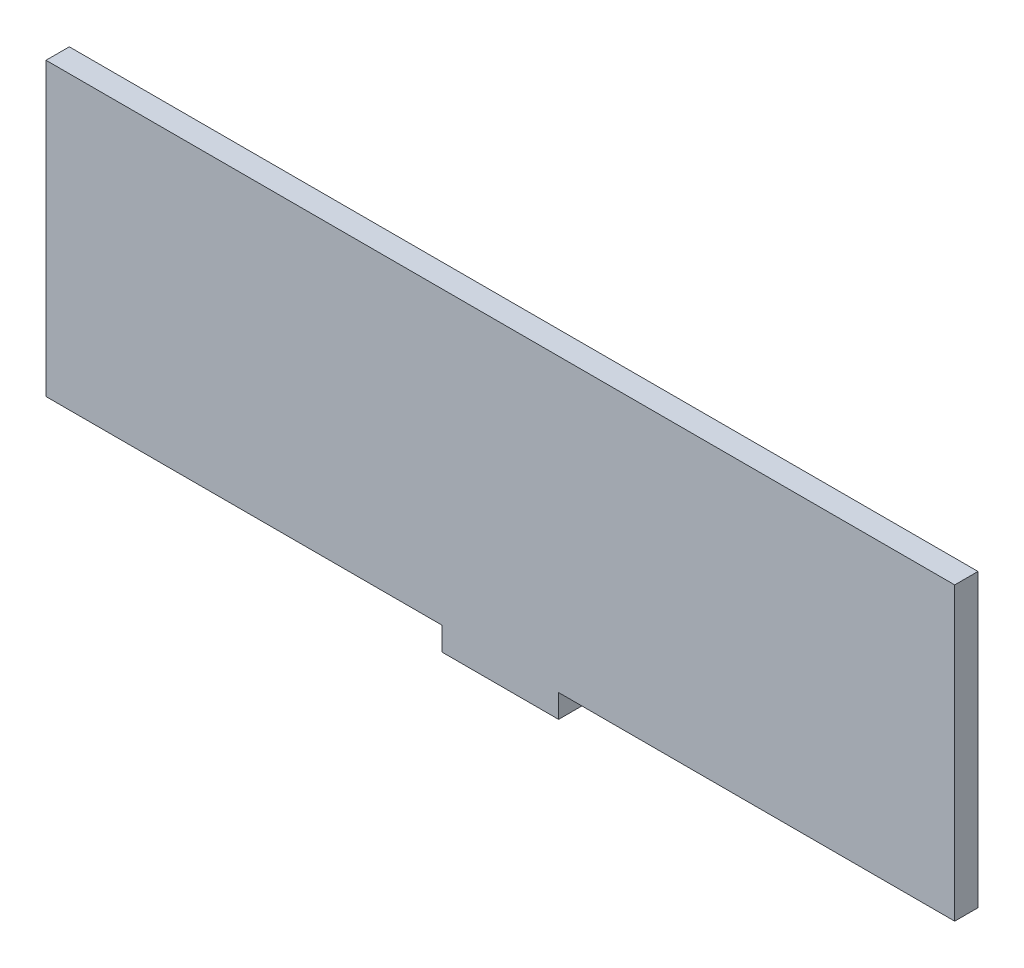
SolidWorks part; units mm, degrees
ref_plane "前视基准面" through (0, 0, 0) normal (0, 0, 1) x (1, 0, 0)
ref_plane "上视基准面" through (0, 0, 0) normal (0, 1, 0) x (1, 0, 0)
ref_plane "右视基准面" through (0, 0, 0) normal (1, 0, 0) x (0, 0, -1)
other "Configuration Table"
sketch "草图1" plane through (0, 0, 0) normal (0, 0, 1) x (1, 0, 0)
  line L0 (-39, 0) -> (39, 0) construction
  line L1 (-39, -12.5) -> (-5, -12.5)
  line L2 (-39, -12.5) -> (-39, 12.5)
  line L3 (-39, 12.5) -> (-5, 12.5)
  line L4 (39, -12.5) -> (39, 12.5)
  line L5 (-39, -12.5) -> (39, 12.5) construction
  line L6 (-39, 12.5) -> (39, -12.5) construction
  line L11 (0, 10.5) -> (5, 12.5) construction
  line L12 (-5, 12.5) -> (0, 10.5) construction
  line L13 (-5, -12.5) -> (5, -14.5) construction
  line L14 (-5, -14.5) -> (5, -12.5) construction
  line L15 (5, -14.5) -> (5, -12.5)
  line L17 (-5, -14.5) -> (-5, -12.5)
  line L18 (-5, -14.5) -> (5, -14.5)
  line L19 (5, 12.5) -> (39, 12.5)
  line L20 (5, -12.5) -> (39, -12.5)
  line L21 (-5, 12.5) -> (5, 12.5)
  point P0 (0, 0)
  point P6 (0, 10.5)
  point P8 (0, -14.5)
  point P10 (5, -14.5)
  point P17 (0, -10.5)
  dimension "D1" = 25
  dimension "D2" = 78
  dimension "D3" = 2
  dimension "D4" = 2
  dimension "D5" = 10
extrude "凸台-拉伸1" add sketch "草图1" along normal blind 2
